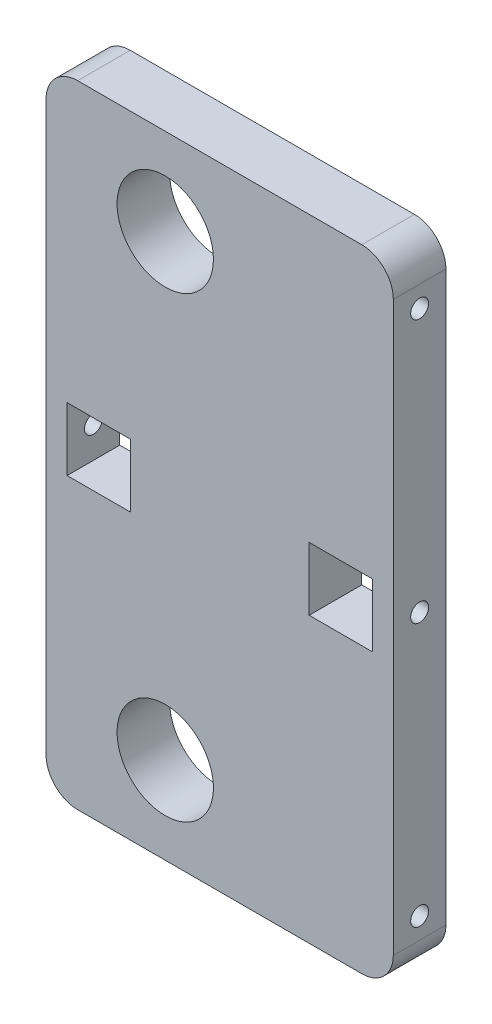
SolidWorks part; units mm, degrees
ref_plane "Front Plane" through (0, 0, 0) normal (0, 0, 1) x (1, 0, 0)
ref_plane "Top Plane" through (0, 0, 0) normal (0, 1, 0) x (1, 0, 0)
ref_plane "Right Plane" through (0, 0, 0) normal (1, 0, 0) x (0, 0, -1)
sketch "Sketch1" plane through (0, 0, 0) normal (0, 0, 1) x (1, 0, 0)
  line L0 (0, 30) -> (0, -30) construction
  line L1 (-16.5, -30) -> (16.5, -30)
  line L2 (-16.5, -30) -> (-16.5, 30)
  line L3 (-16.5, 30) -> (16.5, 30)
  line L4 (16.5, -30) -> (16.5, 30)
  line L5 (-16.5, -30) -> (16.5, 30) construction
  line L6 (-16.5, 30) -> (16.5, -30) construction
  line L7 (-16.5, 0) -> (16.5, 0) construction
  line L19 (14.5, 3) -> (8.5, 3)
  line L20 (-14.5, -3) -> (-8.5, -3)
  line L21 (-14.5, -3) -> (-14.5, 3)
  line L22 (-14.5, 3) -> (-8.5, 3)
  line L23 (-8.5, -3) -> (-8.5, 3)
  line L24 (-14.5, -3) -> (-8.5, 3) construction
  line L25 (-14.5, 3) -> (-8.5, -3) construction
  line L26 (8.5, -3) -> (8.5, 3)
  line L27 (14.5, -3) -> (8.5, -3)
  line L28 (14.5, -3) -> (14.5, 3)
  circle A4 centre (-5.175, 21.75) radius 4.58
  circle A5 centre (-5.175, -21.75) radius 4.58
  point P0 (0, 0)
  point P8 (0, 21.75)
  point P29 (-11.5, 0)
  dimension "D3" = 9.16
  dimension "D4" = 8.25
  dimension "D5" = 11.325
  dimension "D1" = 60
  dimension "D2" = 33
  dimension "D8" = 6
  dimension "D9" = 6
  dimension "D10" = 2
extrude "Boss-Extrude1" add sketch "Sketch1" along normal blind 5
sketch "Sketch2" plane through (16.5, 0, 0) normal (1, 0, 0) x (0, 0, -1)
  line L0 (-2.5, 30) -> (-2.5, -30) construction
  line L1 (-5, 30) -> (0, 30) construction
  line L2 (-5, -30) -> (0, -30) construction
  line L3 (-5, 0) -> (0, 0) construction
  line L4 (-5, -30) -> (-5, 30) construction
  circle A0 centre (-2.5, 0) radius 0.85
  circle A1 centre (-2.5, -25) radius 0.85
  circle A2 centre (-2.5, 25) radius 0.85
  dimension "D1" = 1.7
  dimension "D2" = 1.7
  dimension "D3" = 5
extrude "Cut-Extrude1" cut sketch "Sketch2" against normal blind 3
sketch "Sketch3" plane through (-16.5, 0, 0) normal (-1, 0, 0) x (0, 0, 1)
  line L0 (2.5, 30) -> (2.5, -30) construction
  line L1 (5, 30) -> (0, 30) construction
  line L2 (5, -30) -> (0, -30) construction
  line L3 (0, 0) -> (5, 0) construction
  line L4 (5, 30) -> (5, -30) construction
  circle A0 centre (2.5, 0) radius 0.85
  dimension "D1" = 1.7
extrude "Cut-Extrude2" cut sketch "Sketch3" against normal blind 3
fillet "Fillet1" radius 3 4 edges at (16.5, -30, 2.5) (-16.5, -30, 2.5) (-16.5, 30, 2.5) (16.5, 30, 2.5)
